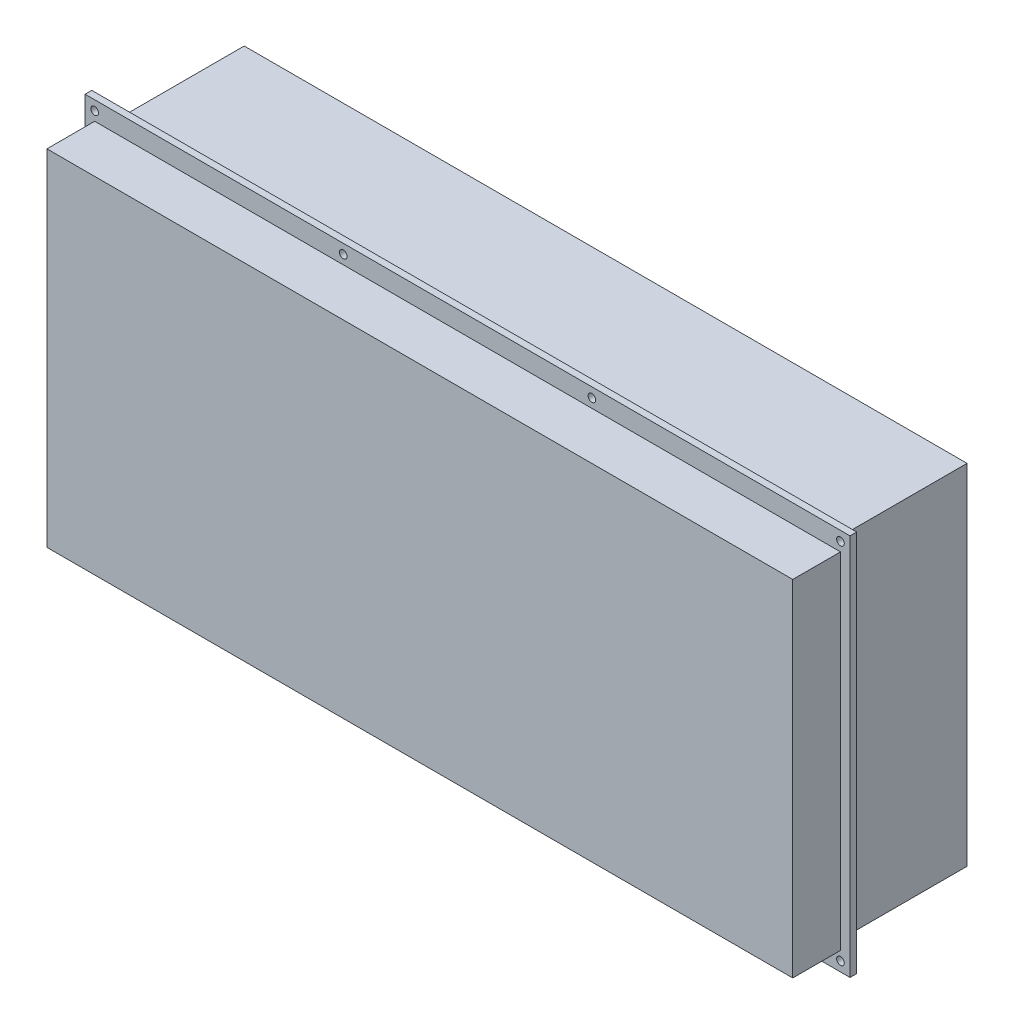
SolidWorks part; units mm, degrees
ref_plane "Ön Düzlem" through (0, 0, 0) normal (0, 0, 1) x (1, 0, 0)
ref_plane "Üst Düzlem" through (0, 0, 0) normal (0, 1, 0) x (1, 0, 0)
ref_plane "Sağ Düzlem" through (0, 0, 0) normal (1, 0, 0) x (0, 0, -1)
sketch "Çizim1" plane through (0, 0, 0) normal (0, 0, 1) x (1, 0, 0)
  line L1 (-200, -100) -> (200, -100)
  line L2 (-200, -100) -> (-200, 100)
  line L3 (-200, 100) -> (200, 100)
  line L4 (200, -100) -> (200, 100)
  line L5 (-200, -100) -> (200, 100) construction
  line L6 (-200, 100) -> (200, -100) construction
  circle A0 centre (-195, 95) radius 2
  circle A1 centre (-65, 95) radius 2
  circle A2 centre (65, 95) radius 2
  circle A3 centre (195, 95) radius 2
  circle A4 centre (-65, -95) radius 2
  circle A5 centre (65, -95) radius 2
  circle A6 centre (195, -95) radius 2
  circle A7 centre (-195, -95) radius 2
  point P0 (0, 0)
  point P8 (-270.333, 185.8722)
  dimension "D3" = 5
  dimension "D5" = 4
  dimension "D1" = 400
  dimension "D2" = 200
  dimension "D4" = 5
  dimension "D6" = 4
  dimension "D7" = 2
extrude "Yükseklik-Ekstrüzyon1" add sketch "Çizim1" along normal mid plane 3.5
sketch "Çizim2" plane through (0, 0, 1.75) normal (0, 0, 1) x (1, 0, 0)
  line L1 (-195, -90.25) -> (195, -90.25)
  line L2 (-195, -90.25) -> (-195, 90.25)
  line L3 (-195, 90.25) -> (195, 90.25)
  line L4 (195, -90.25) -> (195, 90.25)
  line L5 (-195, -90.25) -> (195, 90.25) construction
  line L6 (-195, 90.25) -> (195, -90.25) construction
  point P0 (0, 0)
  dimension "D1" = 180.5
  dimension "D2" = 390
extrude "Yükseklik-Ekstrüzyon2" add sketch "Çizim2" along normal blind 24.953
sketch "Çizim4" plane through (0, 0, -1.75) normal (0, 0, -1) x (-1, 0, 0)
  line L1 (-189, -91.24) -> (189, -91.24)
  line L2 (-189, -91.24) -> (-189, 91.24)
  line L3 (-189, 91.24) -> (189, 91.24)
  line L4 (189, -91.24) -> (189, 91.24)
  line L5 (-189, -91.24) -> (189, 91.24) construction
  line L6 (-189, 91.24) -> (189, -91.24) construction
  point P0 (0, 0)
  dimension "D1" = 378
  dimension "D2" = 182.48
extrude "Yükseklik-Ekstrüzyon4" add sketch "Çizim4" along normal blind 68.7
